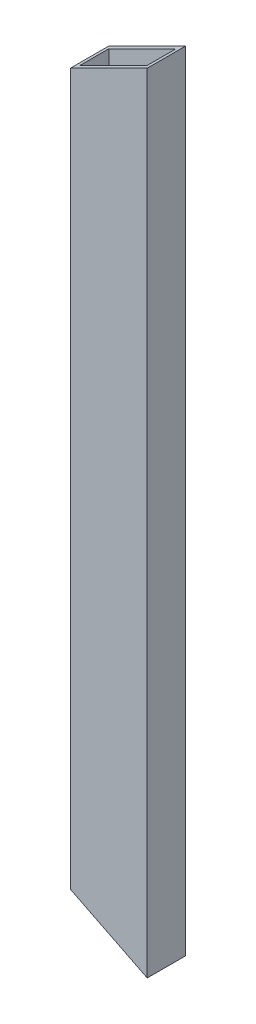
SolidWorks part; units mm, degrees
material "1060 Alloy"
ref_plane "Front Plane" through (0, 0, 0) normal (0, 0, 1) x (1, 0, 0)
ref_plane "Top Plane" through (0, 0, 0) normal (0, 1, 0) x (1, 0, 0)
ref_plane "Right Plane" through (0, 0, 0) normal (1, 0, 0) x (0, 0, -1)
sketch "Sketch1" plane through (0, 0, 0) normal (0, 1, 0) x (1, 0, 0)
  line L1 (-25.4, -12.7) -> (25.4, -12.7)
  line L2 (-25.4, -12.7) -> (-25.4, 12.7)
  line L3 (-25.4, 12.7) -> (25.4, 12.7)
  line L4 (25.4, -12.7) -> (25.4, 12.7)
  line L5 (-25.4, -12.7) -> (25.4, 12.7) construction
  line L6 (-25.4, 12.7) -> (25.4, -12.7) construction
  point P0 (0, 0)
  dimension "D1" = 50.8
  dimension "D2" = 25.4
extrude "Extrude-Thin1" add sketch "Sketch1" along normal blind 520.7 thin thin type one direction reverse wall 3.175
sketch "Sketch2" plane through (0, 0, 12.7) normal (0, 0, 1) x (1, 0, 0)
  line L0 (25.4, 0) -> (-25.4, 25.4)
  line L1 (-25.4, 520.7) -> (-25.4, 0) construction
  line L2 (-25.4, 25.4) -> (-25.4, 0)
  line L3 (-25.4, 0) -> (25.4, 0)
  line L4 (-25.4, 260.35) -> (25.4, 260.35) construction
  line L5 (25.4, 520.7) -> (25.4, 0) construction
  line L6 (-25.4, 520.7) -> (25.4, 520.7)
  line L7 (-25.4, 495.3) -> (-25.4, 520.7)
  line L8 (25.4, 520.7) -> (-25.4, 495.3)
  dimension "D1" = 25.4
extrude "Cut-Extrude1" cut sketch "Sketch2" against normal through all
